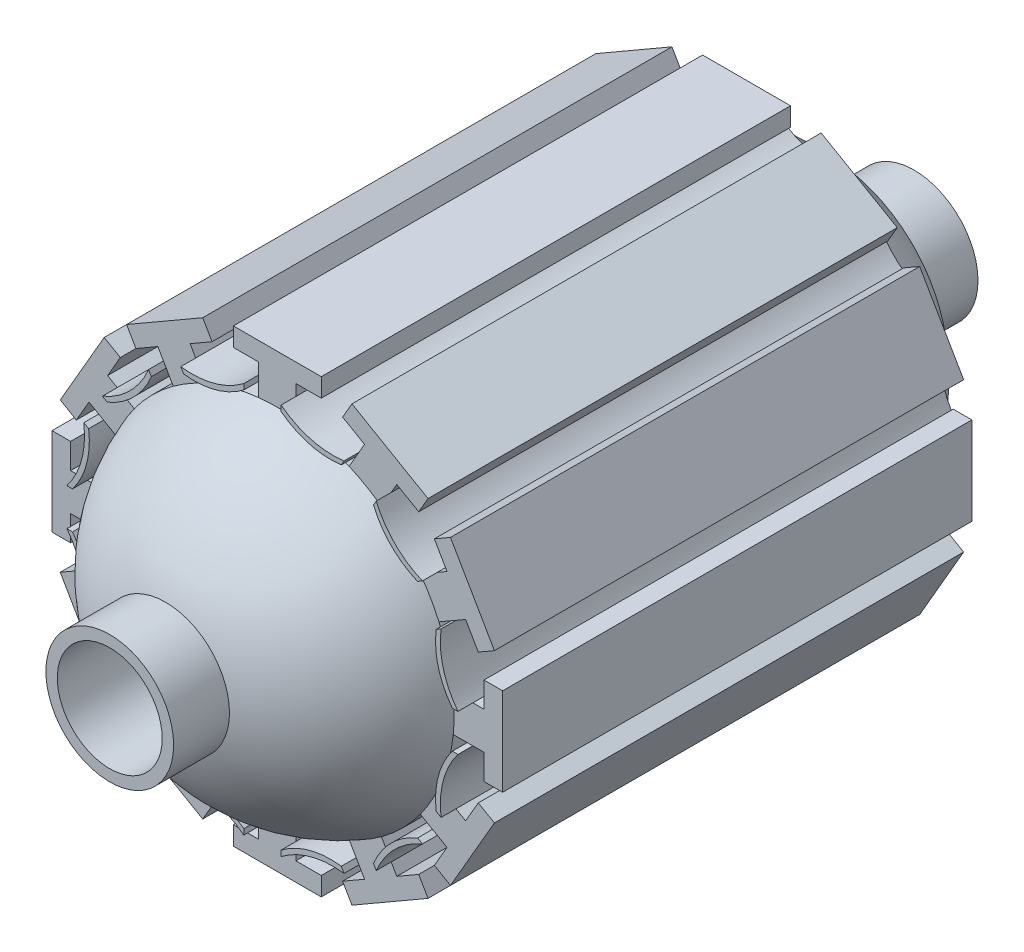
SolidWorks part; units mm, degrees
ref_plane "Front Plane" through (0, 0, 0) normal (0, 0, 1) x (1, 0, 0)
ref_plane "Top Plane" through (0, 0, 0) normal (0, 1, 0) x (1, 0, 0)
ref_plane "Right Plane" through (0, 0, 0) normal (1, 0, 0) x (0, 0, -1)
sketch "Sketch1" plane through (0, 0, 0) normal (0, 0, 1) x (1, 0, 0)
  line L0 (-2.9972, 14.097) -> (-1.27, 14.097)
  line L1 (1.27, 15.367) -> (-1.27, 15.367)
  line L2 (1.27, 15.367) -> (1.27, 0)
  line L3 (1.27, 0) -> (-1.27, 0)
  line L4 (-1.27, 15.367) -> (-1.27, 0)
  line L5 (1.27, 15.367) -> (-1.27, 0) construction
  line L6 (1.27, 0) -> (-1.27, 15.367) construction
  line L7 (-2.9972, 14.097) -> (2.9972, 14.097)
  line L8 (-2.9972, 14.097) -> (-2.9972, 15.367)
  line L9 (-2.9972, 15.367) -> (2.9972, 15.367)
  line L10 (2.9972, 14.097) -> (2.9972, 15.367)
  line L11 (-2.9972, 14.097) -> (2.9972, 15.367) construction
  line L12 (-2.9972, 15.367) -> (2.9972, 14.097) construction
  line L13 (-1.27, 14.097) -> (-1.524, 14.097)
  line L14 (-1.27, 14.097) -> (-1.27, 13.843)
  line L15 (2.9972, 14.097) -> (1.27, 14.097)
  line L16 (1.27, 14.097) -> (1.524, 14.097)
  line L17 (1.27, 14.097) -> (1.27, 13.843)
  arc A0 (-1.524, 14.097) -> (-1.27, 13.843) centre (-1.524, 13.843) cw
  arc A1 (1.524, 14.097) -> (1.27, 13.843) centre (1.524, 13.843) ccw
  point P0 (0, 7.6835)
  point P5 (0, 14.732)
  dimension "D1" = 15.367
  dimension "D2" = 2.54
  dimension "D3" = 5.9944
  dimension "D4" = 1.27
  dimension "D5" = 0.254
  dimension "D6" = 0.254
  dimension "D7" = 0.254
  dimension "D8" = 0.254
extrude "Boss-Extrude1" add sketch "Sketch1" along normal blind 32.004 contours L7 L15 L10 L9 L2 | L4 L7 L2 L1 | L9 L8 L0 L7 L4 | L7 L4 L3 L2
sketch "Sketch2" plane through (0, 0, 0) normal (0, 0, 1) x (1, 0, 0)
  circle A0 centre (0, 0) radius 4.3561
  dimension "D1" = 8.7122
extrude "Boss-Extrude2" add sketch "Sketch2" along normal blind 43.434 and the other way blind 11.43
pattern_circular "CirPattern1" count 12 over 360 about axis through (0, 0, 0) along (0, 0, 1) of "Boss-Extrude1"
sketch "Sketch3" plane through (0, 0, 0) normal (0, 0, 1) x (1, 0, 0)
  line L0 (-1.27, 14.097) -> (-1.27, 13.335)
  line L1 (-1.27, 14.097) -> (-1.27, 4.7397) construction
  line L2 (-5.9486, 12.8434) -> (-5.5676, 12.1834)
  line L4 (-1.27, 13.335) -> (-1.27, 12.954)
  line L5 (-5.5676, 12.1834) -> (-5.3771, 11.8535)
  line L6 (-1.27, 13.335) -> (-4.8089, 17.9469)
  line L7 (-4.8089, 17.9469) -> (-5.5676, 12.1834)
  line L8 (-1.27, 12.954) -> (-4.652, 17.3615)
  line L9 (-4.652, 17.3615) -> (-5.3771, 11.8535)
  line L10 (-5.9486, 12.8434) -> (-1.27, 4.7397) construction
  line L11 (-5.9486, 12.8434) -> (-4.4528, 13.707) construction
  arc A0 (-1.27, 13.335) -> (-5.5676, 12.1834) centre (-4.8089, 17.9469) cw
  arc A1 (-1.27, 12.954) -> (-5.3771, 11.8535) centre (-4.652, 17.3615) cw
  dimension "D1" = 0.762
  dimension "D2" = 0.762
  dimension "D3" = 0.381
  dimension "D4" = 0.381
  dimension "D5" = 45
  dimension "D6" = 45
extrude "Boss-Extrude3" add sketch "Sketch3" along normal blind 33.02 and the other way blind 1.016 contours A1 L8 A0 L9 | L4 A0 L8 | L9 A0 L5
pattern_circular "CirPattern2" count 12 over 360 about axis through (0, 0, 0) along (0, 0, 1) of "Boss-Extrude3"
ref_axis "Axis1" through (0, 0, -11.43) along (0, 0, 1)
sketch "Sketch5" plane through (0, 0, 0) normal (1, 0, 0) x (0, 0, -1)
  line L0 (11.43, 4.3561) -> (0, 4.3561) construction
  line L1 (7.62, 4.3561) -> (0, 4.3561)
  line L2 (0, 4.3561) -> (0, 12.065)
  arc A0 (0, 12.065) -> (7.62, 4.3561) centre (-3.9696, 0.5206) cw
  point P0 (0, 12.065)
  point P1 (7.62, 4.3561)
revolve "Revolve1" add sketch "Sketch5" angle 360 about axis through (0, 0, -11.43) along (0, 0, 1)
ref_plane "Plane1" through (0, 0, 16.002) normal (0, 0, -1) x (-1, 0, 0)
sketch "Sketch6" plane through (0, 0, 0) normal (0, 0, 1) x (1, 0, 0)
  circle A0 centre (0, 0) radius 12.065
extrude "Boss-Extrude4" add sketch "Sketch6" along normal blind 32.004
mirror "Mirror1" about plane through (0, 0, 16.002) normal (0, 0, -1) of "Revolve1"
sketch "Sketch4" plane through (0, 0, 0) normal (0, 0, 1) x (1, 0, 0)
  circle A0 centre (0, 0) radius 3.575
  dimension "D1" = 7.1501
extrude "Cut-Extrude1" cut sketch "Sketch4" against normal through all both and the other way through all
equation "\"D1@Boss-Extrude2\"=1.26+0.45"
